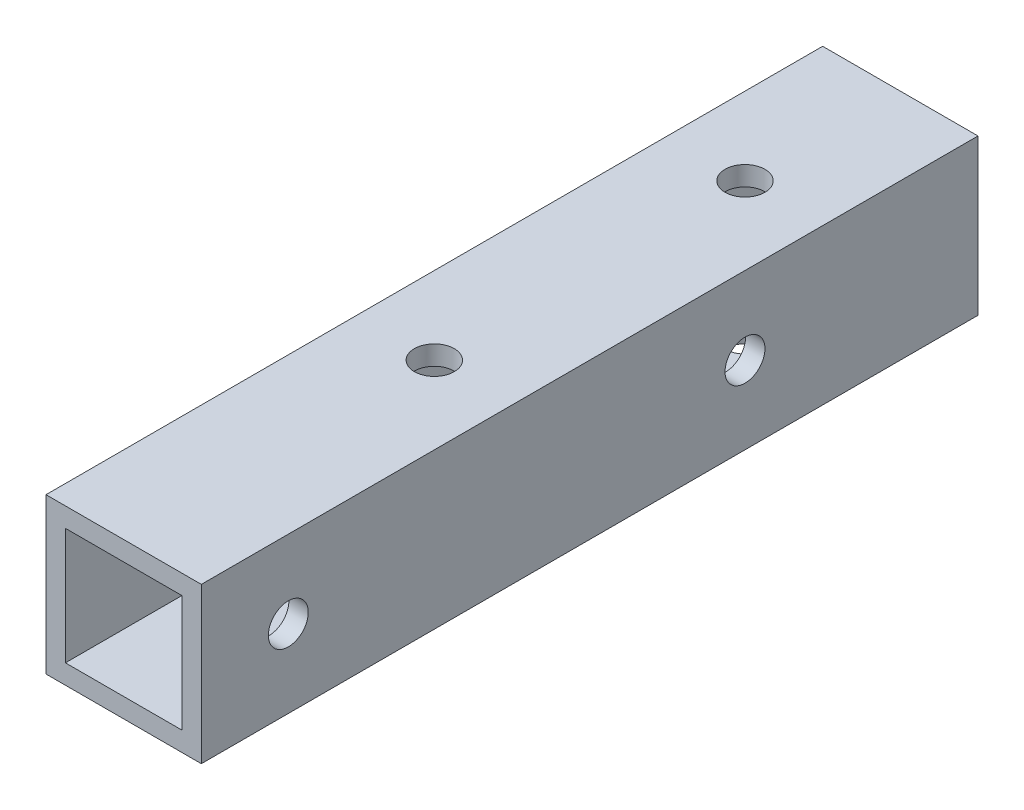
SolidWorks part; units mm, degrees
material "1060 Alloy"
ref_plane "Front Plane" through (0, 0, 0) normal (0, 0, 1) x (1, 0, 0)
ref_plane "Top Plane" through (0, 0, 0) normal (0, 1, 0) x (1, 0, 0)
ref_plane "Right Plane" through (0, 0, 0) normal (1, 0, 0) x (0, 0, -1)
sketch "Sketch2" plane through (0, 0, 0) normal (0, 0, 1) x (1, 0, 0)
  line L1 (12.7, -12.7) -> (-12.7, -12.7)
  line L2 (12.7, -12.7) -> (12.7, 12.7)
  line L3 (12.7, 12.7) -> (-12.7, 12.7)
  line L4 (-12.7, -12.7) -> (-12.7, 12.7)
  line L5 (12.7, -12.7) -> (-12.7, 12.7) construction
  line L6 (12.7, 12.7) -> (-12.7, -12.7) construction
  point P0 (0, 0)
  dimension "D1" = 25.4
extrude "Boss-Extrude1" add sketch "Sketch2" along normal blind 127 contours L4 L3 L2 L1
sketch "Sketch4" plane through (0, 0, 0) normal (0, 0, 1) x (1, 0, 0)
  line L0 (12.7, -12.7) -> (12.7, 12.7) construction
  line L1 (-9.525, -9.525) -> (9.525, -9.525)
  line L2 (-9.525, -9.525) -> (-9.525, 9.525)
  line L3 (-9.525, 9.525) -> (9.525, 9.525)
  line L4 (9.525, -9.525) -> (9.525, 9.525)
  line L5 (-9.525, -9.525) -> (9.525, 9.525) construction
  line L6 (-9.525, 9.525) -> (9.525, -9.525) construction
  line L7 (12.7, 12.7) -> (-12.7, 12.7) construction
  point P0 (0, 0)
  dimension "D1" = 3.175
  dimension "D2" = 3.175
extrude "Cut-Extrude1" cut sketch "Sketch4" along normal through all
sketch "Sketch5" plane through (0, 12.7, 0) normal (0, 1, 0) x (1, 0, 0)
  line L2 (12.7, 0) -> (-12.7, 0) construction
  circle A0 centre (0, -25.4) radius 3.2639
  point P4 (0, 0)
  dimension "D1" = 6.5278
  dimension "D2" = 25.4
extrude "Cut-Extrude2" cut sketch "Sketch5" against normal blind 304.8 contours A0
sketch "Sketch6" plane through (0, 12.7, 0) normal (0, 1, 0) x (1, 0, 0)
  line L0 (12.7, -127) -> (-12.7, -127) construction
  line L1 (12.7, 0) -> (-12.7, 0) construction
  circle A0 centre (0, -76.2) radius 3.2639
  point P4 (0, -127)
  dimension "D1" = 6.5278
  dimension "D2" = 76.2
extrude "Cut-Extrude3" cut sketch "Sketch6" against normal through all
sketch "Sketch7" plane through (-12.7, 0, 0) normal (-1, 0, 0) x (0, 0, 1)
  line L0 (0, -12.7) -> (0, 12.7) construction
  circle A0 centre (38.1, 0) radius 3.2639
  circle A1 centre (112.776, 0) radius 3.2639
  point P6 (0, 0)
  dimension "D1" = 6.5278
  dimension "D2" = 112.776
  dimension "D3" = 38.1
extrude "Cut-Extrude4" cut sketch "Sketch7" against normal through all
